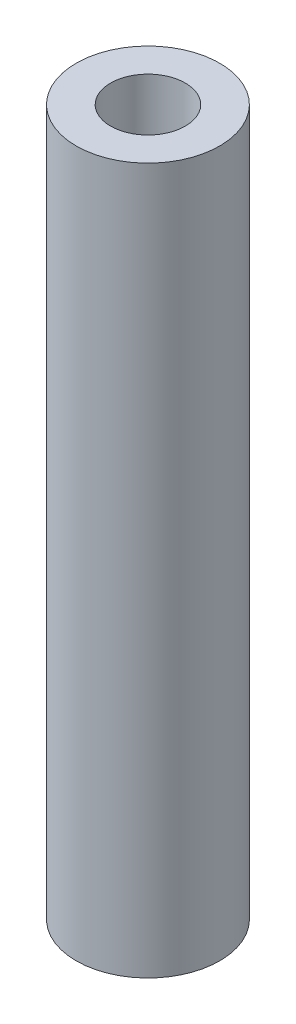
SolidWorks part; units mm, degrees
material "PTFE (general)"
ref_plane "Front Plane" through (0, 0, 0) normal (0, 0, 1) x (1, 0, 0)
ref_plane "Top Plane" through (0, 0, 0) normal (0, 1, 0) x (1, 0, 0)
ref_plane "Right Plane" through (0, 0, 0) normal (1, 0, 0) x (0, 0, -1)
sketch "Sketch1" plane through (0, 0, 0) normal (0, 1, 0) x (1, 0, 0)
  circle A0 centre (0, 0) radius 1.5875
  circle A1 centre (0, 0) radius 3.05
  dimension "D1" = 3.175
  dimension "D2" = 6.1
extrude "Boss-Extrude1" add sketch "Sketch1" along normal mid plane 30
